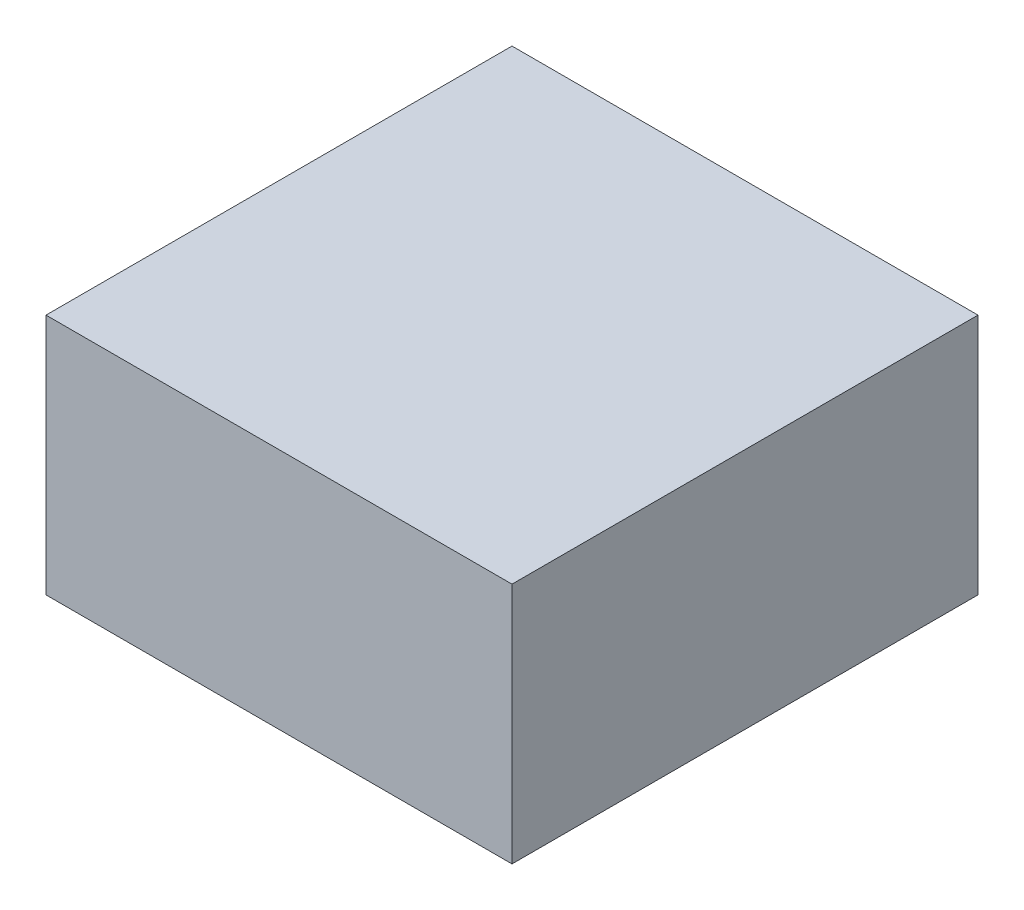
SolidWorks part; units mm, degrees
material "Plain Carbon Steel"
ref_plane "Front Plane" through (0, 0, 0) normal (0, 0, 1) x (1, 0, 0)
ref_plane "Top Plane" through (0, 0, 0) normal (0, 1, 0) x (1, 0, 0)
ref_plane "Right Plane" through (0, 0, 0) normal (1, 0, 0) x (0, 0, -1)
sketch "Sketch1" plane through (0, 0, 0) normal (0, 1, 0) x (1, 0, 0)
  line L1 (-43.1842, 81.7649) -> (83.8158, 81.7649)
  line L2 (-43.1842, 81.7649) -> (-43.1842, -45.2351)
  line L3 (-43.1842, -45.2351) -> (83.8158, -45.2351)
  line L4 (83.8158, 81.7649) -> (83.8158, -45.2351)
  dimension "D1" = 127
  dimension "D2" = 127
extrude "Boss-Extrude1" add sketch "Sketch1" along normal blind 66.04
